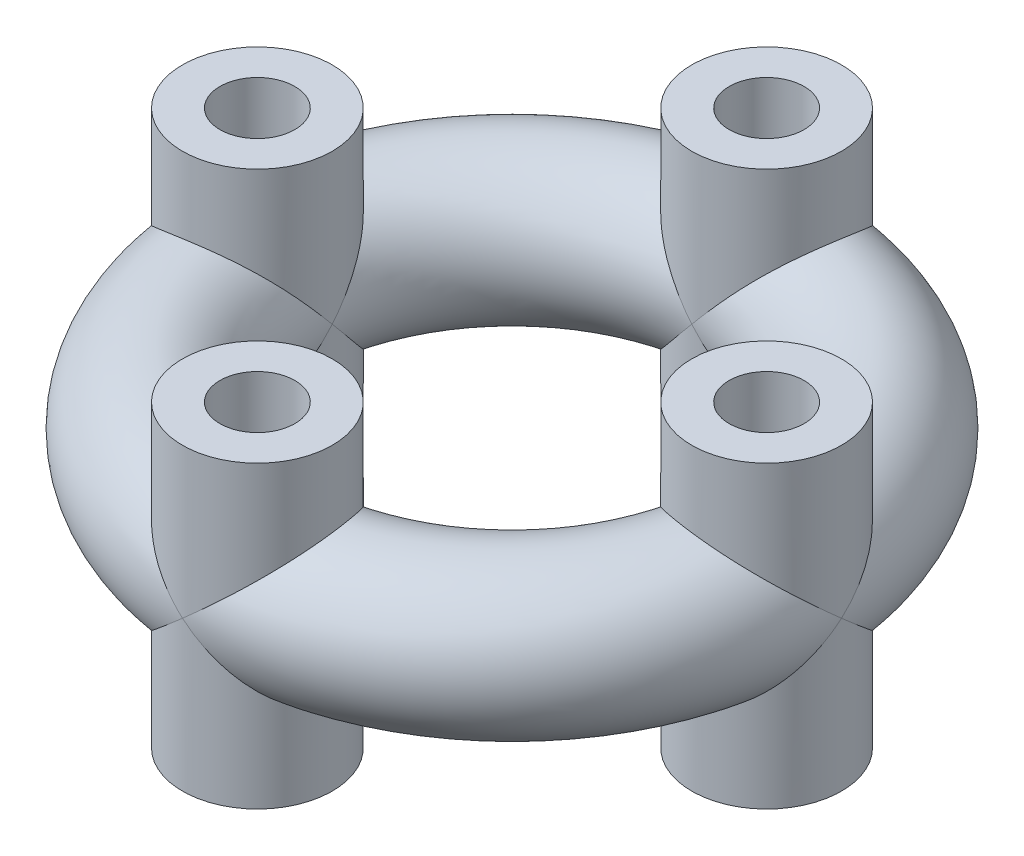
SolidWorks part; units mm, degrees
material "Nylon 101"
ref_plane "Front" through (0, 0, 0) normal (0, 0, 1) x (1, 0, 0)
ref_plane "Top" through (0, 0, 0) normal (0, 1, 0) x (1, 0, 0)
ref_plane "Right" through (0, 0, 0) normal (1, 0, 0) x (0, 0, -1)
sketch "Sketch2" plane through (0, 0, 0) normal (0, 0, 1) x (1, 0, 0)
  line L0 (0, 0) -> (21.59, 0) construction
  line L1 (0, 0) -> (0, 9.2346) construction
  circle A0 centre (21.59, 0) radius 6.35
  dimension "D2" = 12.7
  dimension "D1" = 21.59
revolve "Base Revolve" add sketch "Sketch2" angle 360 about L1
sketch "Sketch4" plane through (0, 0, 0) normal (0, 1, 0) x (1, 0, 0)
  circle A0 centre (0, 21.59) radius 6.35
  dimension "D1" = 12.7
  dimension "D2" = 21.59
extrude "Column" add sketch "Sketch4" along normal mid plane 25.4
sketch "Sketch5" plane through (0, 0, 0) normal (0, 1, 0) x (1, 0, 0)
  circle A0 centre (0, 21.59) radius 3.175
  dimension "D1" = 6.35
extrude "Fastener Hole Cut" cut sketch "Sketch5" against normal through all both and the other way through all
pattern_circular "Column and Hole Pattern" count 4 over 360 about axis through (0, 0, 0) along (0, 1, 0) of "Column", "Fastener Hole Cut"
